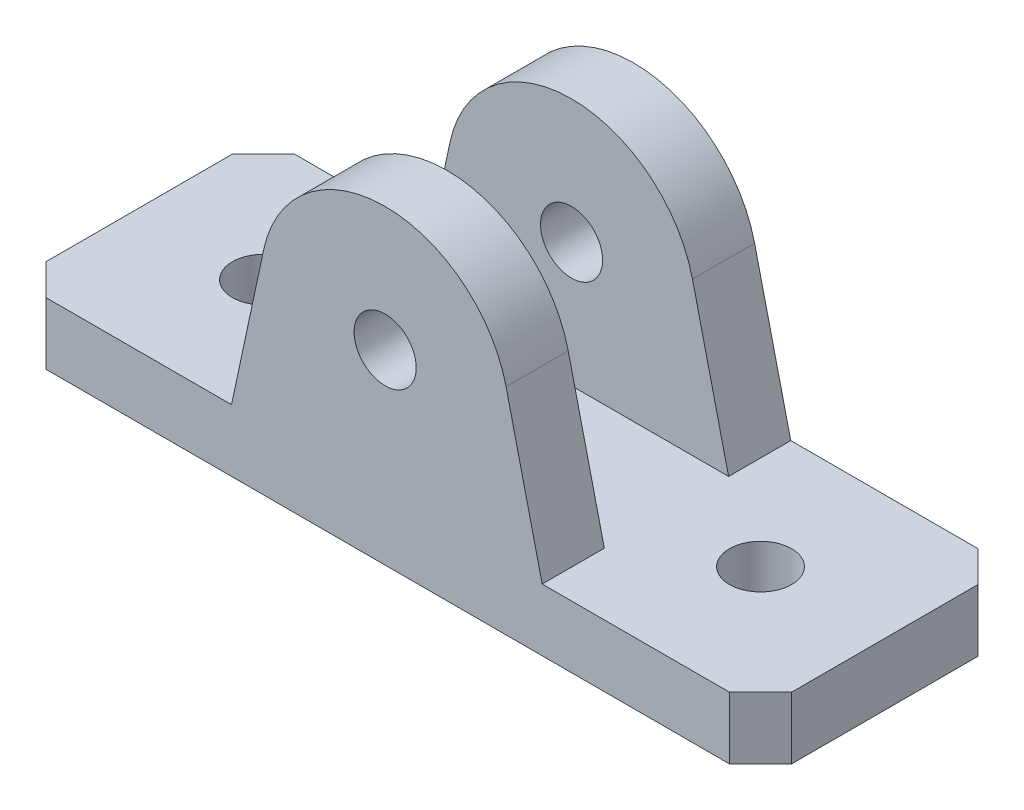
SolidWorks part; units mm, degrees
ref_plane "Front Plane" through (0, 0, 0) normal (0, 0, 1) x (1, 0, 0)
ref_plane "Top Plane" through (0, 0, 0) normal (0, 1, 0) x (1, 0, 0)
ref_plane "Right Plane" through (0, 0, 0) normal (1, 0, 0) x (0, 0, -1)
sketch "Sketch1" plane through (0, 0, 0) normal (0, 1, 0) x (1, 0, 0)
  line L1 (60, -20) -> (-60, -20)
  line L2 (60, -20) -> (60, 20)
  line L3 (60, 20) -> (-60, 20)
  line L4 (-60, -20) -> (-60, 20)
  line L5 (60, -20) -> (-60, 20) construction
  line L6 (60, 20) -> (-60, -20) construction
  point P0 (0, 0)
  dimension "D1" = 120
  dimension "D2" = 40
extrude "Boss-Extrude1" add sketch "Sketch1" along normal blind 10
sketch "Sketch2" plane through (0, 0, 20) normal (0, 0, 1) x (1, 0, 0)
  line L0 (-19.9762, 34.1767) -> (-25.1391, 10)
  line L1 (-60, 10) -> (60, 10) construction
  line L2 (19.0465, 34.6004) -> (24.8609, 10)
  line L3 (24.8609, 10) -> (-25.1391, 10)
  line L4 (-0.4172, 30) -> (0, 0) construction
  arc A0 (-19.9762, 34.1767) -> (19.0465, 34.6004) centre (-0.4172, 30) cw
  circle A1 centre (-0.4172, 30) radius 5
  point P11 (-0.1391, 10)
  dimension "D4" = 20
  dimension "D5" = 10
  dimension "D1" = 50
  dimension "D2" = 30
  dimension "D3" = 24.8609
extrude "Boss-Extrude2" add sketch "Sketch2" against normal blind 10
mirror "Mirror1" about plane through (0, 0, 0) normal (0, 0, 1) of "Boss-Extrude2"
chamfer "Chamfer1" distance 5 angle 45 4 edges at (-60, 5, -20) (-60, 5, 20) (60, 5, -20) (60, 5, 20)
sketch "Sketch3" plane through (0, 10, 0) normal (0, 1, 0) x (1, 0, 0)
  line L2 (-40, 0) -> (40, 0) construction
  circle A0 centre (40, 0) radius 5
  circle A1 centre (-40, 0) radius 5
  point P2 (0, 0)
  dimension "D1" = 10
  dimension "D3" = 10
  dimension "D2" = 80
extrude "Cut-Extrude1" cut sketch "Sketch3" against normal through all
scale "Scale2" bodies to scale 104 scale about centroid uniform scaling yes scale factor 0.5
equation "\"Comprimento\"= 120"
equation "\"D1@Sketch1\"=\"Comprimento\""
equation "\"Largura\"=40"
equation "\"D2@Sketch1\"=\"Largura\""
equation "\"Espessura\"=10"
equation "\"D1@Boss-Extrude1\"=\"Espessura\""
equation "\"DiamFuro\"=10"
equation "\"D5@Sketch2\"=\"DiamFuro\""
equation "\"D2@Sketch3\"=\"Comprimento\"*2/3"
